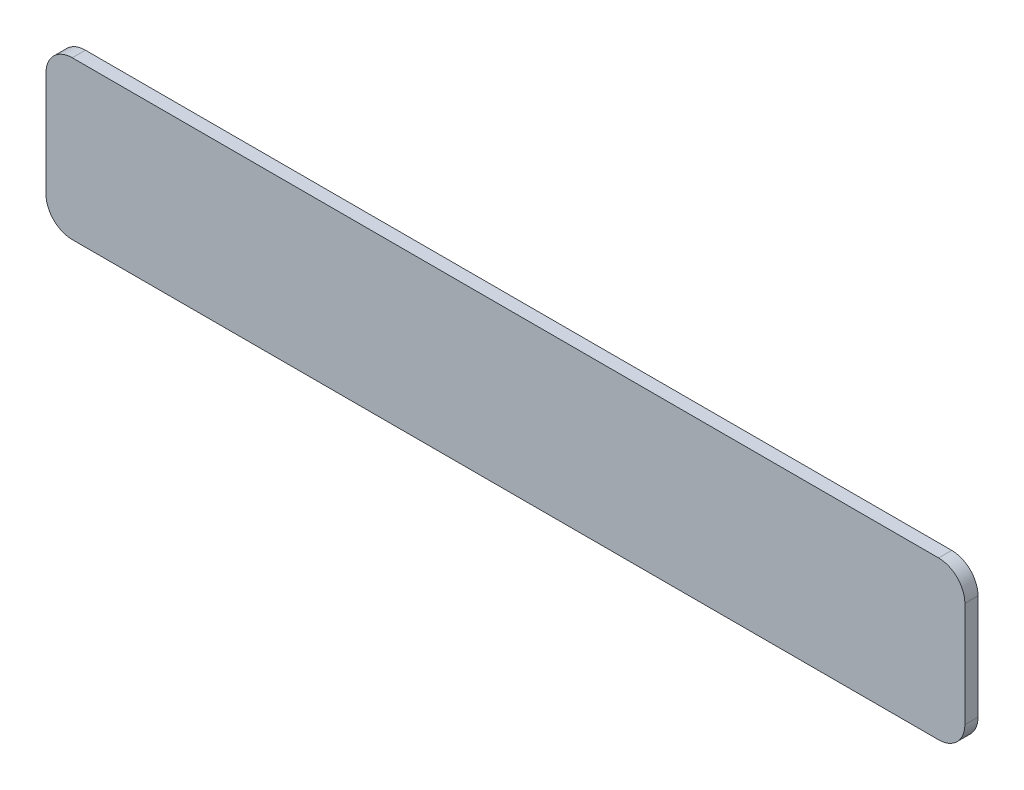
SolidWorks part; units mm, degrees
ref_plane "Front" through (0, 0, 0) normal (0, 0, 1) x (1, 0, 0)
ref_plane "Top" through (0, 0, 0) normal (0, 1, 0) x (1, 0, 0)
ref_plane "Right" through (0, 0, 0) normal (1, 0, 0) x (0, 0, -1)
sketch "Sketch1" plane through (0, 0, 0) normal (0, 0, 1) x (1, 0, 0)
  line L1 (-33, -6) -> (33, -6)
  line L2 (-35, -4) -> (-35, 4)
  line L3 (-33, 6) -> (33, 6)
  line L4 (35, -4) -> (35, 4)
  line L5 (-35, -6) -> (35, 6) construction
  line L6 (-35, 6) -> (35, -6) construction
  arc A0 (33, -6) -> (35, -4) centre (33, -4) ccw
  arc A1 (-35, 4) -> (-33, 6) centre (-33, 4) cw
  arc A2 (-33, -6) -> (-35, -4) centre (-33, -4) cw
  arc A3 (33, 6) -> (35, 4) centre (33, 4) cw
  point P0 (0, 0)
  dimension "D3" = 2
  dimension "D1" = 70
  dimension "D2" = 12
extrude "Boss-Extrude1" add sketch "Sketch1" along normal blind 1
